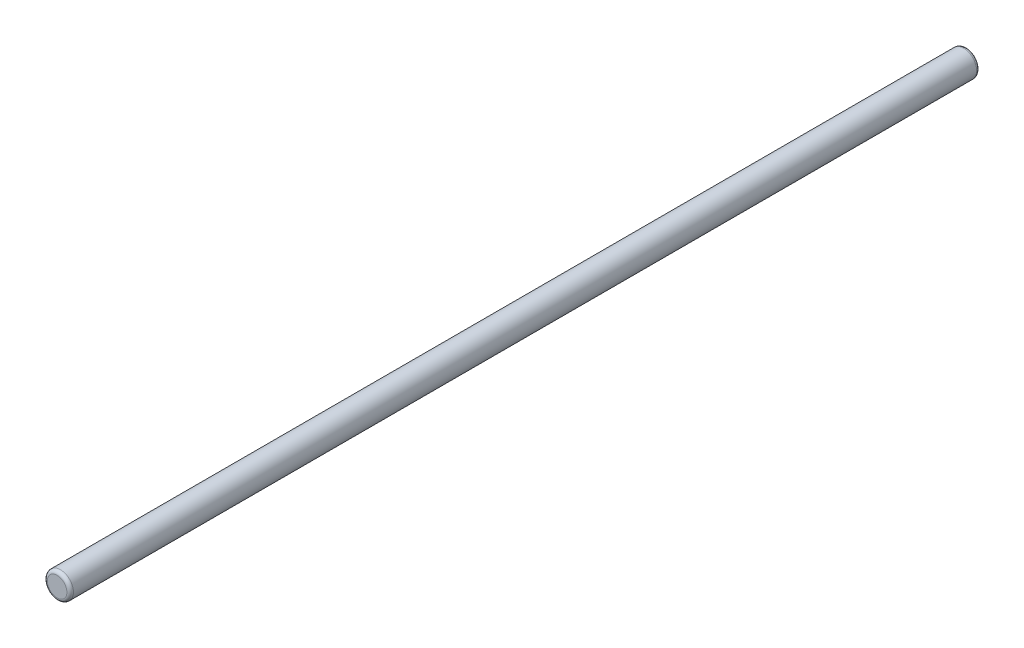
SolidWorks part; units mm, degrees
material "1060 Alloy"
ref_plane "Front Plane" through (0, 0, 0) normal (0, 0, 1) x (1, 0, 0)
ref_plane "Top Plane" through (0, 0, 0) normal (0, 1, 0) x (1, 0, 0)
ref_plane "Right Plane" through (0, 0, 0) normal (1, 0, 0) x (0, 0, -1)
sketch "Sketch1" plane through (0, 0, 0) normal (0, 0, 1) x (1, 0, 0)
  circle A0 centre (0, 0) radius 1.0046
  dimension "D1" = 2.0091
extrude "Boss-Extrude1" add sketch "Sketch1" along normal blind 69.977
fillet "Fillet1" radius 0.254 2 edges at (1.0046, 0, 0) (1.0046, 0, 69.977)
